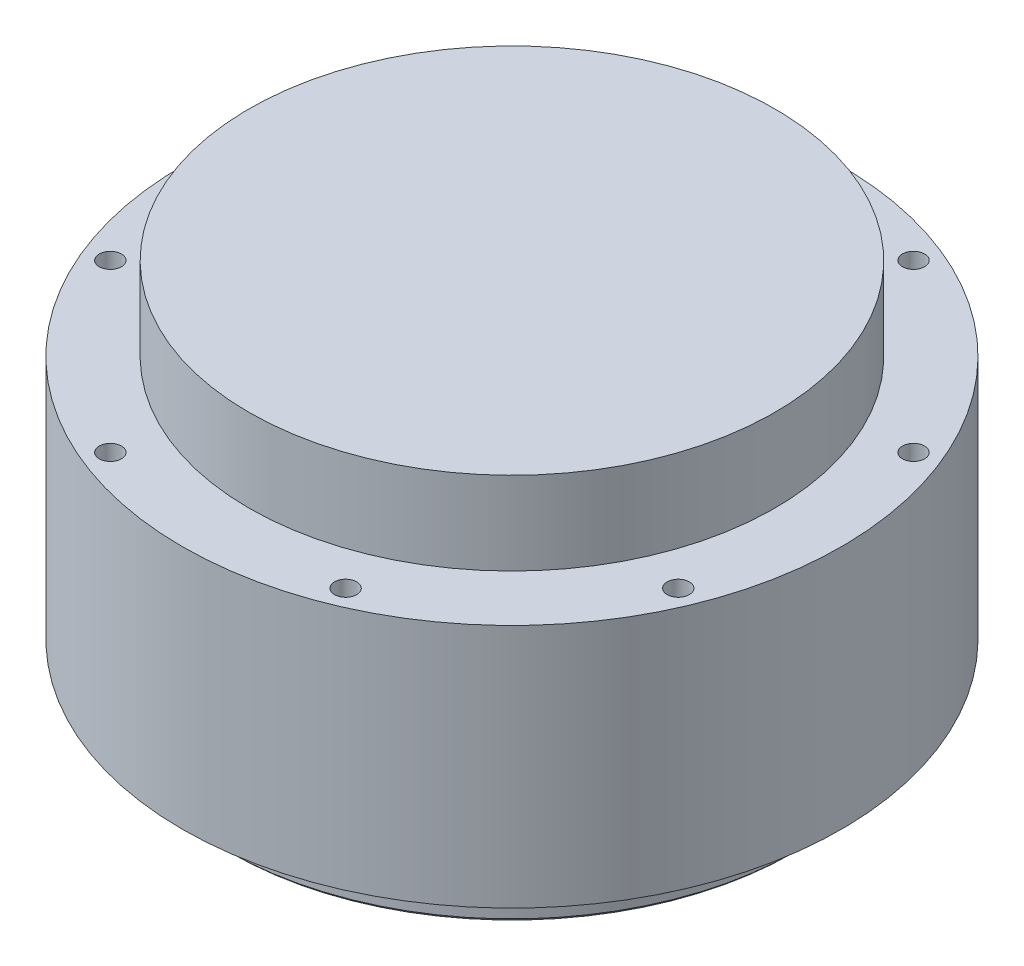
SolidWorks part; units mm, degrees
ref_plane "Спереди" through (0, 0, 0) normal (0, 0, 1) x (1, 0, 0)
ref_plane "Сверху" through (0, 0, 0) normal (0, 1, 0) x (1, 0, 0)
ref_plane "Справа" through (0, 0, 0) normal (1, 0, 0) x (0, 0, -1)
sketch "Эскиз1" plane through (0, 0, 0) normal (0, 1, 0) x (1, 0, 0)
  line L0 (0, 0) -> (0, 41.5) construction
  line L1 (15.8814, 38.341) -> (0, 0) construction
  circle A0 centre (0, 0) radius 44.5
  circle A1 centre (0, 0) radius 41.5 construction
  circle A2 centre (15.8814, 38.341) radius 1.5
  circle A3 centre (38.341, 15.8814) radius 1.5
  circle A4 centre (38.341, -15.8814) radius 1.5
  circle A5 centre (15.8814, -38.341) radius 1.5
  circle A6 centre (-15.8814, -38.341) radius 1.5
  circle A7 centre (-38.341, -15.8814) radius 1.5
  circle A8 centre (-38.341, 15.8814) radius 1.5
  circle A9 centre (-15.8814, 38.341) radius 1.5
  point P24 (0, 0)
  dimension "D1" = 89
  dimension "D2" = 83
  dimension "D3" = 3
  dimension "D4" = 22.5
  dimension "D5" = 8
extrude "Бобышка-Вытянуть1" add sketch "Эскиз1" along normal blind 33.05
sketch "Эскиз2" plane through (0, 33.05, 0) normal (0, 1, 0) x (1, 0, 0)
  circle A0 centre (0, 0) radius 35.5
  dimension "D1" = 71
extrude "Бобышка-Вытянуть2" add sketch "Эскиз2" along normal blind 11.2
sketch "Эскиз3" plane through (0, 0, 0) normal (0, -1, 0) x (1, 0, 0)
  circle A0 centre (0, 0) radius 38.5
  dimension "D1" = 77
extrude "Бобышка-Вытянуть3" add sketch "Эскиз3" along normal blind 6
chamfer "Фаска1" distance 0.5 angle 45 1 edges at (0, -6, -38.5)
sketch "Эскиз5" plane through (0, -6, 0) normal (0, -1, 0) x (1, 0, 0)
  circle A0 centre (0, 0) radius 17.5
  dimension "D1" = 35
extrude "Вырез-Вытянуть1" cut sketch "Эскиз5" against normal blind 15
